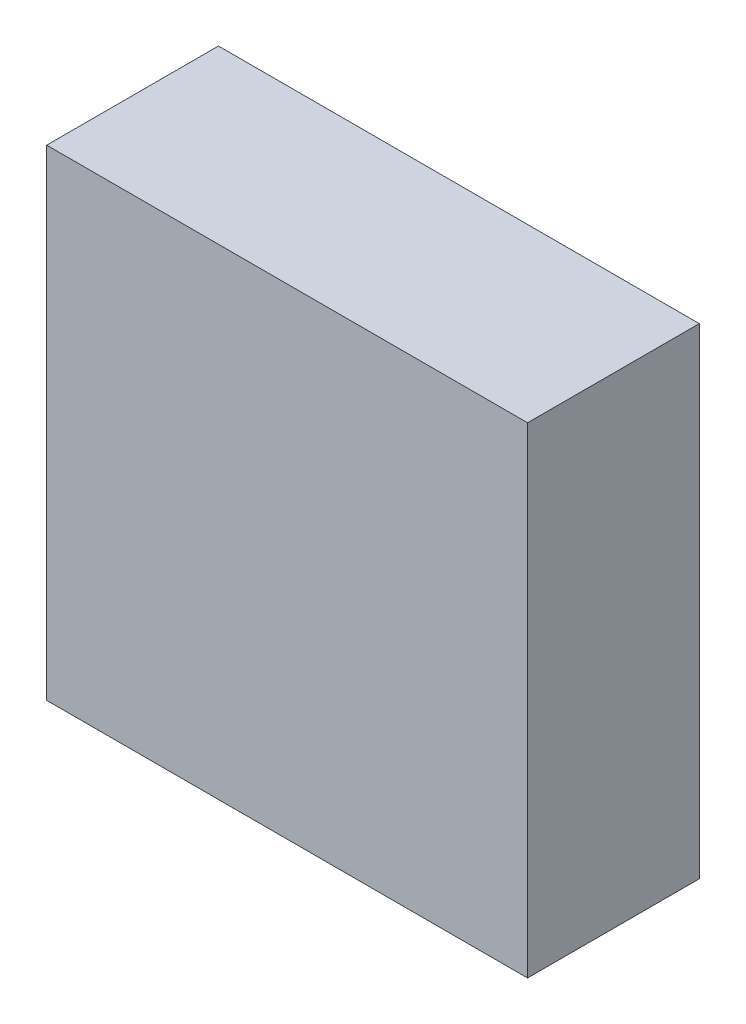
SolidWorks part; units mm, degrees
ref_plane "Front Plane" through (0, 0, 0) normal (0, 0, 1) x (1, 0, 0)
ref_plane "Top Plane" through (0, 0, 0) normal (0, 1, 0) x (1, 0, 0)
ref_plane "Right Plane" through (0, 0, 0) normal (1, 0, 0) x (0, 0, -1)
sketch "Sketch1" plane through (0, 0, 0) normal (0, 0, 1) x (1, 0, 0)
  line L1 (-35, -35) -> (35, -35)
  line L2 (-35, -35) -> (-35, 35)
  line L3 (-35, 35) -> (35, 35)
  line L4 (35, -35) -> (35, 35)
  line L5 (-35, -35) -> (35, 35) construction
  line L6 (-35, 35) -> (35, -35) construction
  point P0 (0, 0)
  dimension "D1" = 70
extrude "Boss-Extrude1" add sketch "Sketch1" along normal blind 25
